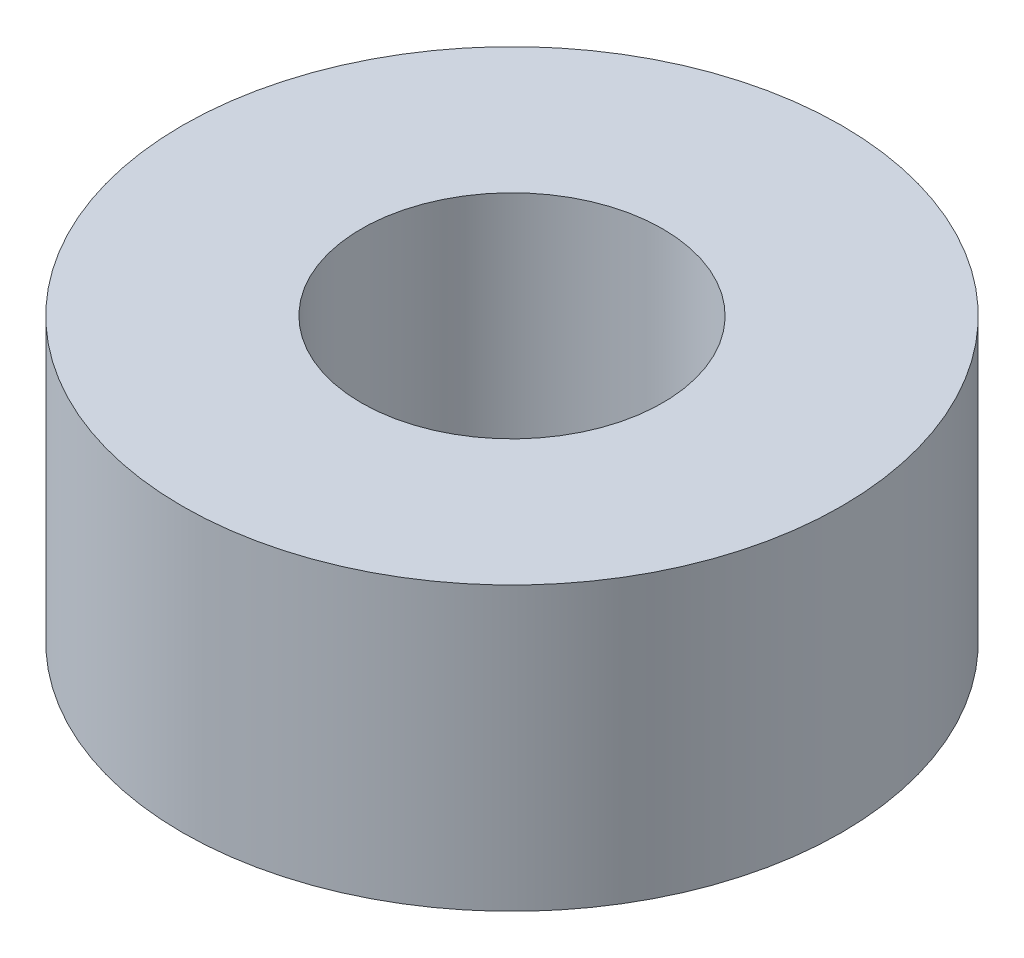
SolidWorks part; units mm, degrees
ref_plane "Alzado" through (0, 0, 0) normal (0, 0, 1) x (1, 0, 0)
ref_plane "Planta" through (0, 0, 0) normal (0, 1, 0) x (1, 0, 0)
ref_plane "Vista lateral" through (0, 0, 0) normal (1, 0, 0) x (0, 0, -1)
sketch "Croquis1" plane through (0, 0, 0) normal (0, 1, 0) x (1, 0, 0)
  circle A0 centre (0, 0) radius 1.6
  circle A1 centre (0, 0) radius 3.5
  dimension "D1" = 3.2
  dimension "D2" = 7
extrude "Saliente-Extruir1" add sketch "Croquis1" along normal blind 3
